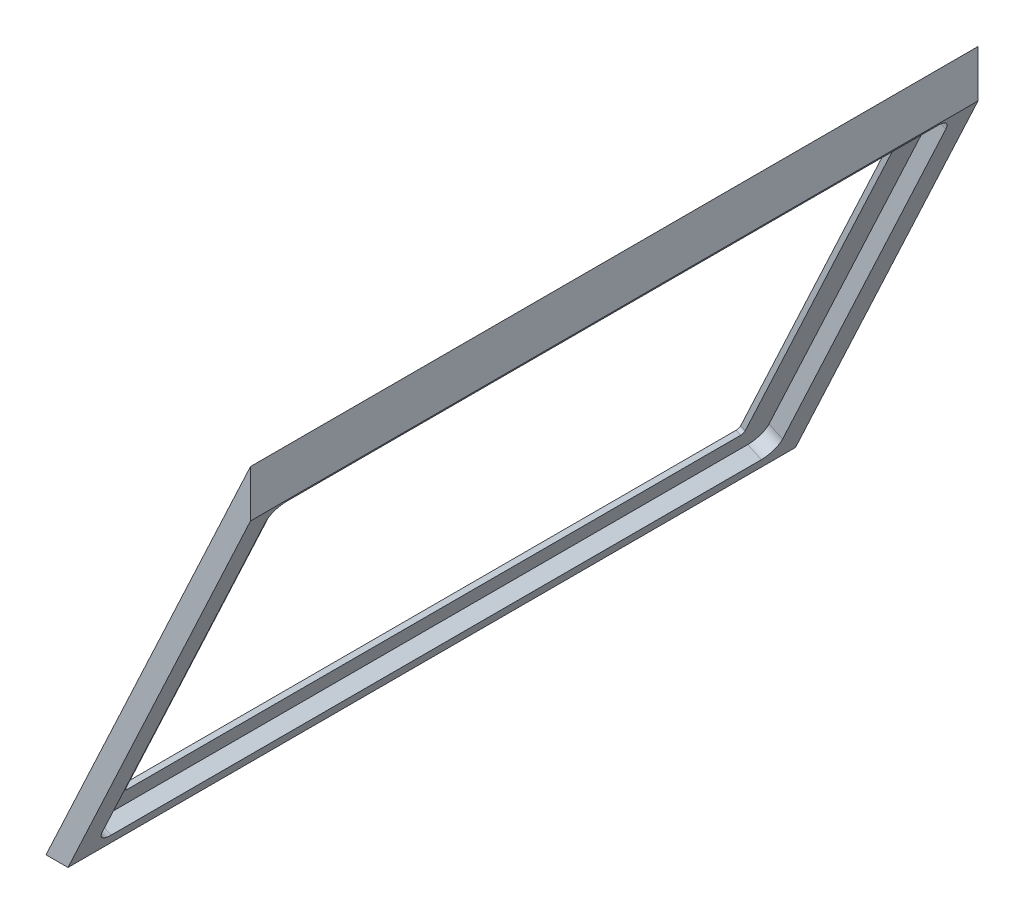
SolidWorks part; units mm, degrees
material "MDF"
ref_plane "Front Plane" through (0, 0, 0) normal (0, 0, 1) x (1, 0, 0)
ref_plane "Top Plane" through (0, 0, 0) normal (0, 1, 0) x (1, 0, 0)
ref_plane "Right Plane" through (0, 0, 0) normal (1, 0, 0) x (0, 0, -1)
sketch "Sketch1" plane through (0, 0, 0) normal (0, 0, 1) x (1, 0, 0)
  line L0 (0, 0) -> (65.1432, 139.7)
  line L1 (65.1432, 139.7) -> (65.1432, 124.6746)
  line L3 (65.1432, 124.6746) -> (7.0064, 0)
  line L4 (7.0064, 0) -> (0, 0)
  line L5 (55, 0) -> (-55, 0) construction
  line L6 (0, -55) -> (0, 55) construction
  dimension "D1" = 6.35
  dimension "D2" = 65
  dimension "D3" = 139.7
extrude "Boss-Extrude1" add sketch "Sketch1" along normal mid plane 231.775
sketch "Sketch2" plane through (0, 0, 0) normal (-0.9063, 0.4226, 0) x (0, 0, 1)
  line L1 (-98.679, 15.9442) -> (-98.679, 128.7202)
  line L3 (97.663, 14.9282) -> (-97.663, 14.9282)
  line L6 (-97.663, 129.7362) -> (97.663, 129.7362)
  line L7 (98.679, 128.7202) -> (98.679, 15.9442)
  line L8 (115.8875, 154.1419) -> (-115.8875, 154.1419) construction
  line L9 (-115.8875, 154.1419) -> (-115.8875, 0) construction
  arc A1 (-98.679, 15.9442) -> (-97.663, 14.9282) centre (-97.663, 15.9442) ccw
  arc A5 (-97.663, 129.7362) -> (-98.679, 128.7202) centre (-97.663, 128.7202) ccw
  arc A6 (98.679, 128.7202) -> (97.663, 129.7362) centre (97.663, 128.7202) ccw
  arc A7 (97.663, 14.9282) -> (98.679, 15.9442) centre (97.663, 15.9442) ccw
  dimension "D1" = 1.016
  dimension "D2" = 197.358
  dimension "D3" = 114.808
  dimension "D4" = 24.4057
  dimension "D5" = 17.2085
extrude "Cut-Extrude1" cut sketch "Sketch2" against normal up to next
sketch "Sketch3" plane through (5.7551, -2.6836, 0) normal (0.9063, -0.4226, 0) x (0, 0, -1)
  line L2 (-107.1563, 138.2102) -> (106.3625, 138.2102)
  line L3 (-107.1563, 8.829) -> (-107.1563, 138.2102)
  line L6 (106.3625, 138.2102) -> (106.3625, 8.829)
  line L7 (106.3625, 8.829) -> (-107.1563, 8.829)
  line L8 (0, 35.8287) -> (0, -35.8287) construction
  line L9 (-97.663, 14.9282) -> (97.663, 14.9282) construction
  dimension "D1" = 213.5188
  dimension "D2" = 129.3812
  dimension "D3" = 107.1562
  dimension "D4" = 6.0992
extrude "Cut-Extrude3" cut sketch "Sketch3" against normal offset from surface (4.7625 mm away) 1.5875 up to face at (30.5689, 65.5552, 0)
fillet "Fillet1" radius 3.175 4 edges at (7.3282, 6.3245, 107.1563) (7.3282, 6.3245, -106.3625) (62.0071, 123.5837, -106.3625) (62.0071, 123.5837, 107.1563)
sketch "Sketch4" plane through (5.7551, -2.6836, 0) normal (0.9063, -0.4226, 0) x (0, 0, -1)
  line L0 (-103.9813, 8.829) -> (103.1875, 8.829) construction
  line L1 (-103.9813, 8.829) -> (103.1875, 8.829)
  line L2 (-107.1563, 12.004) -> (-107.1563, 135.0352) construction
  line L3 (103.1875, 138.2102) -> (-103.9813, 138.2102) construction
  line L4 (106.3625, 12.004) -> (106.3625, 135.0352) construction
  line L5 (-107.1563, 12.004) -> (-107.1563, 135.0352)
  line L6 (103.1875, 138.2102) -> (-103.9813, 138.2102)
  line L7 (106.3625, 12.004) -> (106.3625, 135.0352)
  line L8 (107.95, 12.004) -> (107.95, 135.0352)
  line L9 (103.1875, 139.7977) -> (-103.9813, 139.7977)
  line L10 (-108.7438, 12.004) -> (-108.7438, 135.0352)
  line L11 (-103.9813, 7.2415) -> (103.1875, 7.2415)
  arc A0 (-107.1563, 12.004) -> (-103.9813, 8.829) centre (-103.9813, 12.004) ccw construction
  arc A1 (-107.1563, 12.004) -> (-103.9813, 8.829) centre (-103.9813, 12.004) ccw
  arc A2 (-103.9813, 138.2102) -> (-107.1563, 135.0352) centre (-103.9813, 135.0352) ccw construction
  arc A3 (106.3625, 135.0352) -> (103.1875, 138.2102) centre (103.1875, 135.0352) ccw construction
  arc A4 (103.1875, 8.829) -> (106.3625, 12.004) centre (103.1875, 12.004) ccw construction
  arc A5 (-103.9813, 138.2102) -> (-107.1563, 135.0352) centre (-103.9813, 135.0352) ccw
  arc A6 (106.3625, 135.0352) -> (103.1875, 138.2102) centre (103.1875, 135.0352) ccw
  arc A7 (103.1875, 8.829) -> (106.3625, 12.004) centre (103.1875, 12.004) ccw
  arc A8 (103.1875, 7.2415) -> (107.95, 12.004) centre (103.1875, 12.004) ccw
  arc A9 (107.95, 135.0352) -> (103.1875, 139.7977) centre (103.1875, 135.0352) ccw
  arc A10 (-103.9813, 139.7977) -> (-108.7438, 135.0352) centre (-103.9813, 135.0352) ccw
  arc A11 (-108.7438, 12.004) -> (-103.9813, 7.2415) centre (-103.9813, 12.004) ccw
  dimension "D1" = 1.5875
extrude "Cut-Extrude4" cut sketch "Sketch4" against normal up to surface (4.7625 mm away) up to face at (32.5095, 65.9605, 0.3969)
